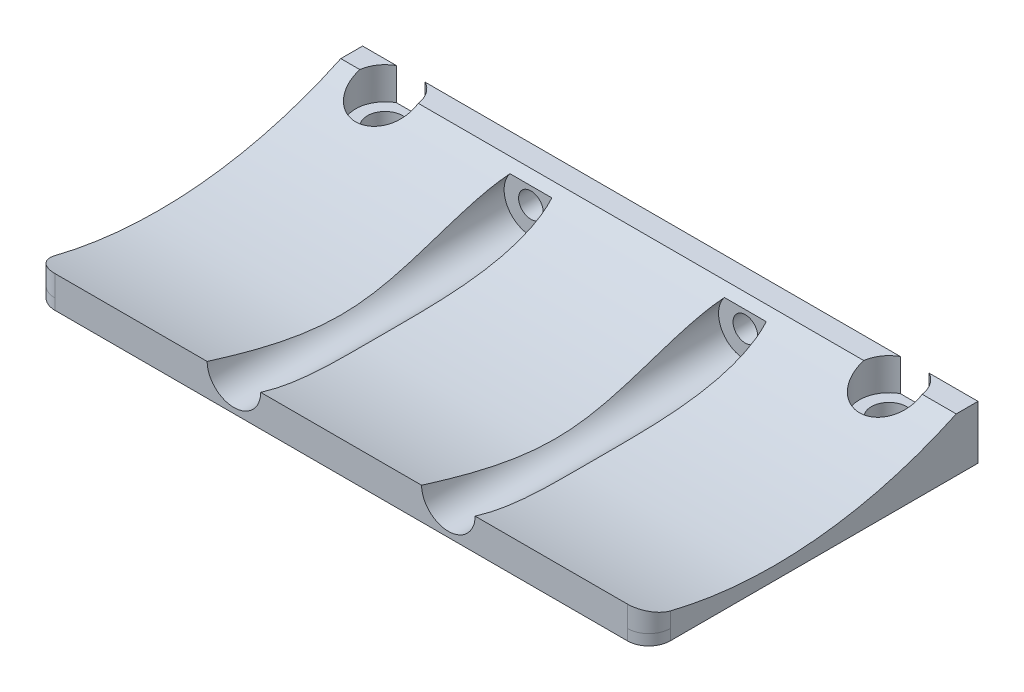
SolidWorks part; units mm, degrees
ref_plane "Front Plane" through (0, 0, 0) normal (0, 0, 1) x (1, 0, 0)
ref_plane "Top Plane" through (0, 0, 0) normal (0, 1, 0) x (1, 0, 0)
ref_plane "Right Plane" through (0, 0, 0) normal (1, 0, 0) x (0, 0, -1)
sketch "Sketch1" plane through (0, 0, 0) normal (0, 1, 0) x (1, 0, 0)
  line L0 (4.5, 28.3) -> (4.5, 4.7) construction
  line L1 (0, 0) -> (57.4, 0)
  line L2 (0, 0) -> (0, 33)
  line L3 (0, 33) -> (57.4, 33)
  line L4 (57.4, 0) -> (57.4, 33)
  circle A0 centre (4.5, 28.3) radius 1.65
  circle A1 centre (51.5, 28.3) radius 1.65
  circle A2 centre (4.5, 4.7) radius 1.65
  circle A3 centre (51.5, 4.7) radius 1.65
  point P13 (0, 16.5)
  point P14 (4.5, 16.5)
  dimension "D3" = 3.3
  dimension "D4" = 47
  dimension "D5" = 23.6
  dimension "D6" = 4.5
  dimension "D1" = 57.4
  dimension "D2" = 33
extrude "Boss-Extrude1" add sketch "Sketch1" along normal blind 1
sketch "Sketch2" plane through (0, 1, 0) normal (0, 1, 0) x (1, 0, 0)
  line L0 (57.4, 0) -> (57.4, 33) construction
  line L1 (0, 33) -> (57.4, 33)
  line L2 (0, 33) -> (0, 30.7)
  line L3 (0, 30.7) -> (57.4, 30.7)
  line L4 (57.4, 33) -> (57.4, 30.7)
  dimension "D1" = 2.3
extrude "Cut-Extrude1" cut sketch "Sketch2" against normal up to next
sketch "Sketch3" plane through (57.4, 0, 0) normal (1, 0, 0) x (0, 0, -1)
  line L0 (30.7, 1) -> (30.7, 5)
  line L1 (30.7, 5) -> (28.7, 5)
  line L2 (28.7, 5) -> (20.7, 1)
  line L3 (0, 1) -> (30.7, 1) construction
  line L4 (20.7, 1) -> (30.7, 1)
  dimension "D1" = 4
  dimension "D2" = 10
  dimension "D3" = 2
extrude "Boss-Extrude2" add sketch "Sketch3" against normal up to surface (57.4 mm away) up to face at (0, 0.5, -15.35)
fillet "Fillet1" radius 2 2 edges at (0, 0.5, 0) (57.4, 0.5, 0)
sketch "Sketch10" plane through (0, 0, 0) normal (1, 0, 0) x (0, 0, -1)
  line L0 (2, 1) -> (0, 1) construction
  line L1 (0, 1) -> (0, 0) construction
  line L2 (0, 0) -> (2, 0) construction
  line L3 (20.7, 1) -> (2, 1) construction
  line L4 (2, 0) -> (30.7, 0) construction
  line L5 (30.7, 0) -> (30.7, 5) construction
  line L6 (30.7, 5) -> (28.7, 5) construction
  line L7 (28.7, 5) -> (20.7, 1) construction
  line L8 (2, 1) -> (0, 1)
  line L9 (0, 1) -> (0, 0)
  line L10 (0, 0) -> (2, 0)
  line L11 (20.7, 1) -> (2, 1)
  line L12 (2, 0) -> (30.7, 0)
  line L13 (30.7, 0) -> (30.7, 5)
  line L14 (30.7, 5) -> (28.7, 5)
  line L15 (28.7, 5) -> (20.7, 1)
  line L16 (0, 1) -> (0, 2.9741)
  line L17 (28.7, 5) -> (28.6687, 5)
  circle A0 centre (11.703, 41.2238) radius 40
  dimension "D1" = 80
extrude "Boss-Extrude3" add sketch "Sketch10" along direction (-1, 0, 0) on the side of the normal up to surface (57.4 mm away) contours A0 L16 L8 L11 L15 L17
sketch "Sketch4" plane through (0, 0, 0) normal (0, -1, 0) x (-1, 0, 0)
  circle A0 centre (-4.5, 28.3) radius 1.65
  circle A1 centre (-51.5, 28.3) radius 1.65
  dimension "D1" = 3.3
extrude "Cut-Extrude2" cut sketch "Sketch4" against normal blind 2
sketch "Sketch5" plane through (0, 2, 0) normal (0, -1, 0) x (-1, 0, 0)
  circle A0 centre (-4.5, 28.3) radius 2.75
  circle A1 centre (-51.5, 28.3) radius 2.75
  dimension "D1" = 5.5
extrude "Cut-Extrude3" cut sketch "Sketch5" against normal up to next
sketch "Sketch6" plane through (0, 0, -30.7) normal (0, 0, -1) x (-1, 0, 0)
  circle A0 centre (-38.7, 3) radius 1.15
  circle A1 centre (-18.7, 3) radius 1.15
  dimension "D1" = 2.3
extrude "Cut-Extrude4" cut sketch "Sketch6" against normal blind 3
sketch "Sketch9" plane through (0, 0, -27.7) normal (0, 0, -1) x (-1, 0, 0)
  circle A0 centre (-38.7, 3) radius 2.5
  circle A1 centre (-18.7, 3) radius 2.5
  dimension "D1" = 5
extrude "Cut-Extrude5" cut sketch "Sketch9" against normal through all
fillet "Fillet2" radius 2 2 edges at (0, 1.9871, 0) (57.4, 1.9871, 0)
